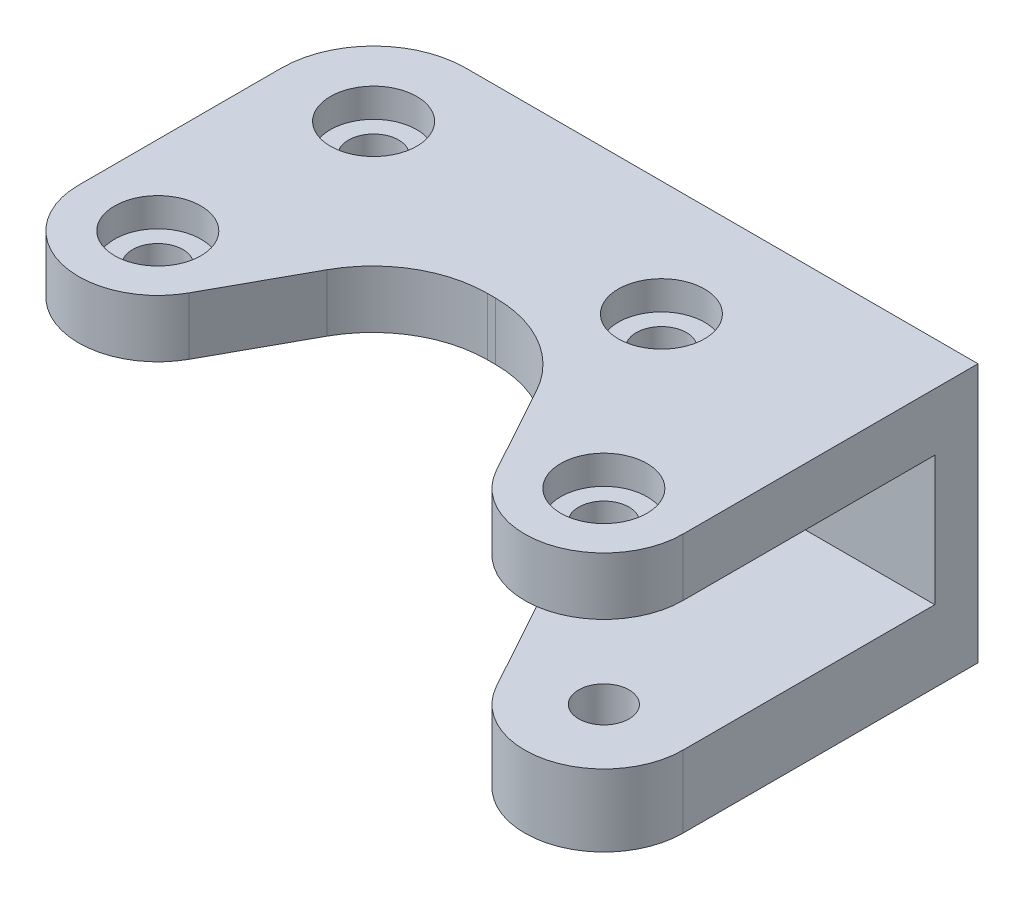
SolidWorks part; units mm, degrees
material "ABS"
ref_plane "Front Plane" through (0, 0, 0) normal (0, 0, 1) x (1, 0, 0)
ref_plane "Top Plane" through (0, 0, 0) normal (0, 1, 0) x (1, 0, 0)
ref_plane "Right Plane" through (0, 0, 0) normal (1, 0, 0) x (0, 0, -1)
sketch "Sketch1" plane through (0, 0, 0) normal (0, 1, 0) x (1, 0, 0)
  line L0 (-21, 0) -> (21, 0)
  line L1 (-21, 0) -> (-21, -20.5)
  line L3 (21, -20.5) -> (21, 0)
  line L6 (-5, -12.81) -> (5, -12.81)
  line L7 (-5, -12.81) -> (-10.6795, -23.1482)
  line L9 (10.6795, -23.1482) -> (5, -12.81)
  arc A0 (10.6795, -23.1482) -> (21, -20.5) centre (15.5, -20.5) ccw
  circle A1 centre (15.5, -20.5) radius 1.75
  circle A2 centre (-15.5, -20.5) radius 1.75
  arc A3 (-21, -20.5) -> (-10.6795, -23.1482) centre (-15.5, -20.5) ccw
  point P3 (0, 0)
  point P5 (22.095, -23.1482)
  point P10 (0, -12.81)
  point P12 (0, 0)
  point P15 (0, 0)
  point P16 (19.2255, -23.1482)
  point P20 (0, 0)
  point P21 (0, 0)
  point P22 (23.9721, -20.5)
  point P23 (20.8237, -22.021)
  dimension "D2" = 3.5
  dimension "D3" = 5.5
  dimension "D4" = 20.5
  dimension "D6" = 31
  dimension "D7" = 12.81
  dimension "D8" = 15.5
  dimension "D9" = 10
  dimension "D10" = 5.5
  dimension "D11" = 28.783
extrude "Boss-Extrude1" add sketch "Sketch1" along normal blind 18
sketch "Sketch2" plane through (0, 18, 0) normal (0, 1, 0) x (1, 0, 0)
  circle A0 centre (-15.5, -20.5) radius 3
  circle A1 centre (15.5, -20.5) radius 3
  dimension "D1" = 6
extrude "Cut-Extrude1" cut sketch "Sketch2" against normal blind 2
sketch "Sketch4" plane through (0, 0, 0) normal (0, 0, -1) x (-1, 0, 0)
  line L1 (-21, 14) -> (21, 14)
  line L2 (-21, 14) -> (-21, 5)
  line L3 (-21, 5) -> (21, 5)
  line L4 (21, 14) -> (21, 5)
  line L5 (21, 18) -> (21, 0) construction
  line L6 (-10.6795, 18) -> (-21, 18) construction
  line L7 (-21, 0) -> (-10.6795, 0) construction
  line L8 (-21, 18) -> (-21, 0) construction
  dimension "D1" = 4
  dimension "D2" = 5
extrude "Cut-Extrude2" cut sketch "Sketch4" against normal through all from offset 3 offset against normal yes
sketch "Sketch6" plane through (0, 0, 0) normal (0, -1, 0) x (1, 0, 0)
  line L0 (5, 12.81) -> (-2.0375, 0)
  line L1 (5, 12.81) -> (10.6795, 23.1482) construction
  line L2 (-21, 0) -> (-2.0375, 0)
  line L3 (-21, 0) -> (-21, 20.5) construction
  line L5 (-21, 0) -> (-21, 28.2726)
  line L6 (-21, 28.2726) -> (5, 28.2726)
  line L7 (5, 28.2726) -> (5, 12.81)
  line L8 (21, 0) -> (-21, 0) construction
extrude "Cut-Extrude3" cut sketch "Sketch6" against normal up to surface (14 mm away) up to face at (15.5, 14, 22.25)
fillet "Fillet1" radius 8 2 edges at (-5, 16, 12.81) (5, 16, 12.81)
sketch "Sketch7" plane through (0, 14, 0) normal (0, -1, 0) x (1, 0, 0)
  line L0 (0, 0) -> (0, 4.3406)
  line L1 (0, 4.3406) -> (-2.0375, 0)
  line L2 (-2.0375, 0) -> (0, 0)
  point P3 (0, 3)
  point P6 (0, 4.3406)
extrude "Cut-Extrude4" cut sketch "Sketch7" along normal through all
sketch "Sketch8" plane through (0, 0, 0) normal (0, 0, -1) x (-1, 0, 0)
  line L0 (0, 14) -> (-25.269, 14) construction
  line L1 (2.4004, 5) -> (-24.539, 5) construction
  line L2 (-21, 0) -> (0, 0) construction
  line L3 (-21, 18) -> (-21, 0) construction
  circle A0 centre (-14, 9.5) radius 1.75
  dimension "D1" = 3.5
  dimension "D3" = 4.5
  dimension "D4" = 7
  dimension "D2" = 5
extrude "Cut-Extrude5" cut sketch "Sketch8" against normal blind 7
sketch "Sketch9" plane through (0, 18, 0) normal (0, 1, 0) x (1, 0, 0)
  line L0 (-21, 0) -> (-21, -20.5) construction
  line L1 (21, 0) -> (-21, 0) construction
  line L2 (21, -20.5) -> (21, 0) construction
  circle A0 centre (7, -8) radius 1.75
  circle A1 centre (-14.59, -6.41) radius 1.75
  dimension "D3" = 3.5
  dimension "D1" = 6.41
  dimension "D2" = 6.41
  dimension "D4" = 14
  dimension "D5" = 8
extrude "Cut-Extrude6" cut sketch "Sketch9" against normal blind 10
sketch "Sketch10" plane through (0, 18, 0) normal (0, 1, 0) x (1, 0, 0)
  circle A0 centre (7, -8) radius 3
  circle A1 centre (-14.59, -6.41) radius 3
  dimension "D1" = 6
extrude "Cut-Extrude7" cut sketch "Sketch10" against normal blind 2
sketch "Sketch11" plane through (0, 0, 0) normal (0, 0, -1) x (-1, 0, 0)
  circle A0 centre (-14, 9.5) radius 3
  point P2 (0, 0)
  point P3 (-14, 9.5)
  dimension "D1" = 6
extrude "Cut-Extrude8" cut sketch "Sketch11" against normal blind 1
fillet "Fillet2" radius 6.41 1 edges at (-21, 16, 0)
equation "\"D8@Sketch1\"=\"D6@Sketch1\"/2"
equation "\"D3@Sketch1\"=\"D10@Sketch1\""
equation "\"D2@Sketch9\"=\"D1@Sketch9\""
